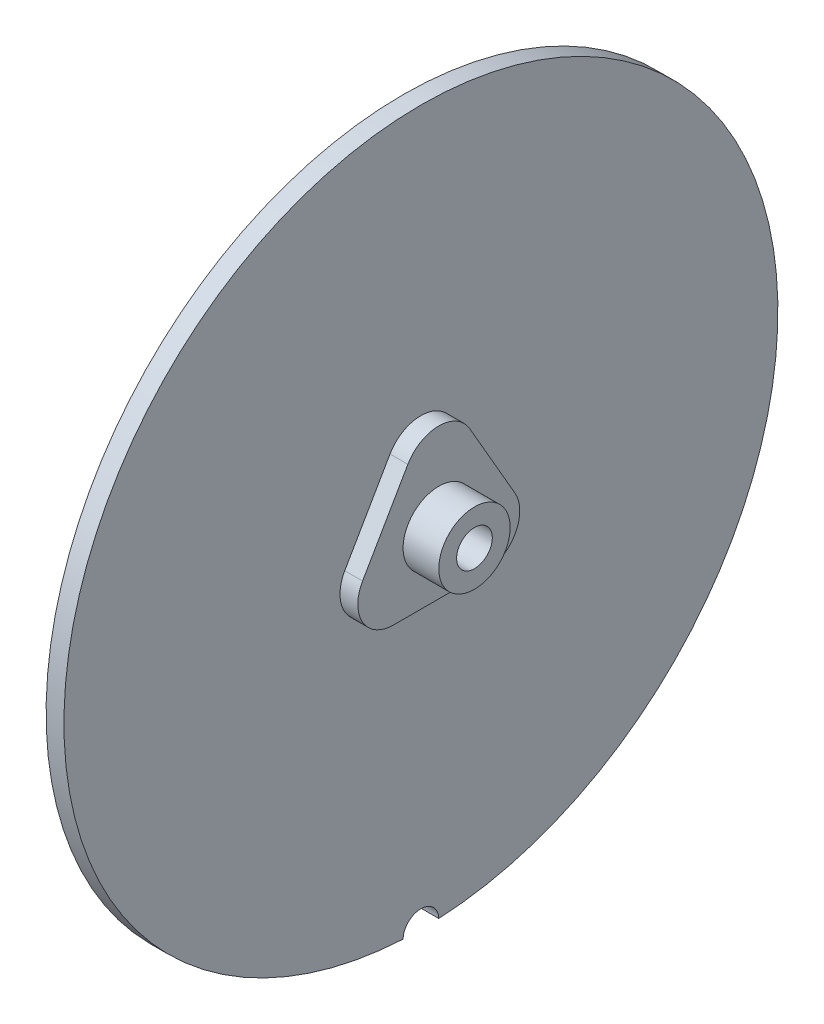
SolidWorks part; units mm, degrees
material "CMR DEFAULT - CHANGE MATERIAL"
ref_plane "XY PLANE - TOP" through (0, 0, 0) normal (0, 0, 1) x (1, 0, 0)
ref_plane "XZ PLANE - SIDE" through (0, 0, 0) normal (0, 1, 0) x (1, 0, 0)
ref_plane "YZ PLANE - FRONT" through (0, 0, 0) normal (1, 0, 0) x (0, 0, -1)
sketch "Sketch1" plane through (0, 0, 0) normal (1, 0, 0) x (0, 0, -1)
  arc A0 (3.174, -63.4206) -> (-3.174, -63.4206) centre (0, 0) ccw
  arc A1 (3.174, -63.4206) -> (-3.174, -63.4206) centre (0, -63.5) ccw
  circle A2 centre (0, 0) radius 3.175
  dimension "D1" = 127
  dimension "D2" = 6.35
  dimension "D3" = 6.35
extrude "Boss-Extrude1" add sketch "Sketch1" along normal blind 3.175 contours A1 A0 A2
sketch "Sketch3" plane through (3.175, 0, 0) normal (1, 0, 0) x (0, 0, -1)
  line L3 (0, 21.997) -> (-19.05, -10.9985)
  line L4 (0, 55) -> (0, -55) construction
  line L7 (-19.05, -10.9985) -> (19.05, -10.9985)
  line L11 (19.05, -10.9985) -> (0, 21.997)
  line L12 (-19.05, -10.9985) -> (0, 0) construction
  line L13 (0, 0) -> (0, 21.997) construction
  line L14 (0, 0) -> (19.05, -10.9985) construction
  circle A1 centre (0, 0) radius 3.175 construction
  circle A2 centre (0, 0) radius 3.175
  dimension "D1" = 38.1
extrude "Boss-Extrude2" add sketch "Sketch3" along normal blind 3.175
sketch "Sketch4" plane through (6.35, 0, 0) normal (1, 0, 0) x (0, 0, -1)
  circle A0 centre (0, 0) radius 6.35
  circle A1 centre (0, 0) radius 3.175 construction
  circle A2 centre (0, 0) radius 3.175
  dimension "D1" = 12.7
extrude "Boss-Extrude3" add sketch "Sketch4" along normal blind 6.35
fillet "Fillet1" radius 6.35 3 edges at (4.7625, 21.997, 0) (4.7625, -10.9985, 19.05) (4.7625, -10.9985, -19.05)
